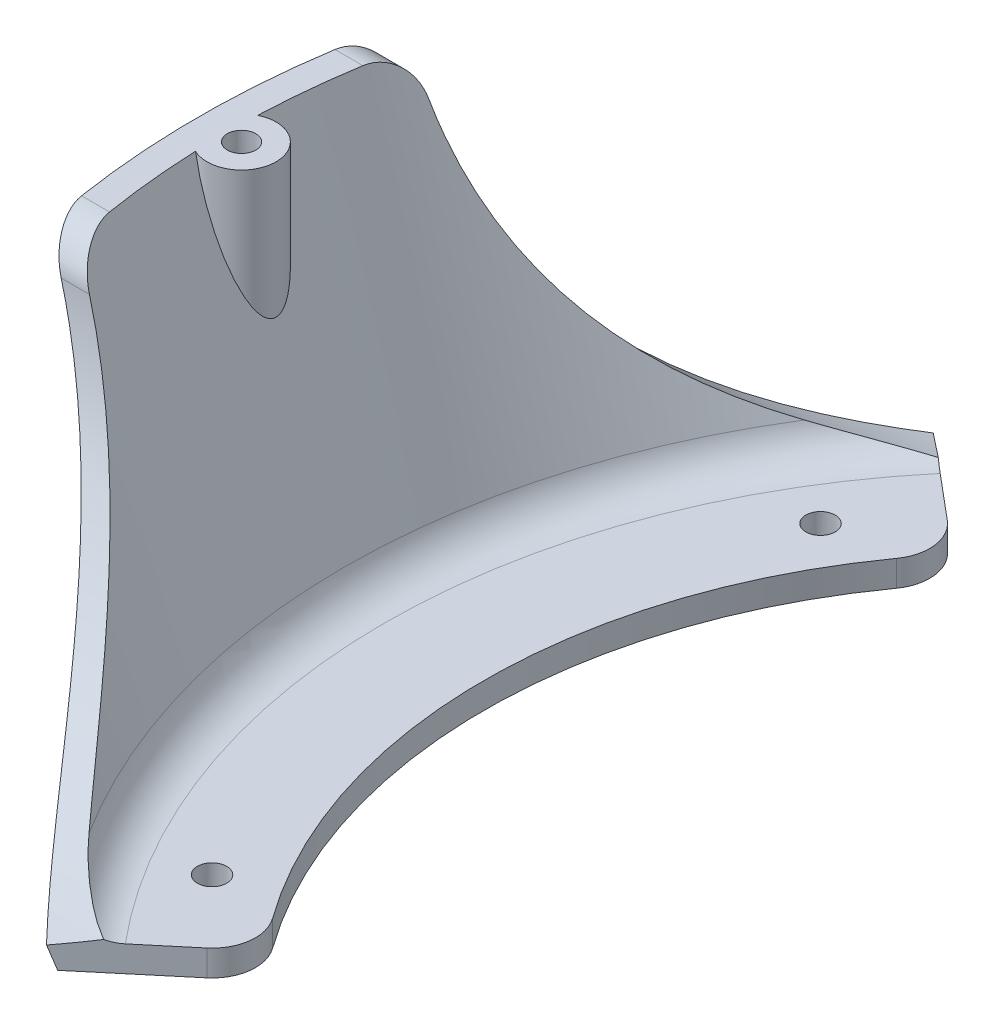
SolidWorks part; units mm, degrees
ref_plane "Plan de face" through (0, 0, 0) normal (0, 0, 1) x (1, 0, 0)
ref_plane "Plan de dessus" through (0, 0, 0) normal (0, 1, 0) x (1, 0, 0)
ref_plane "Plan de droite" through (0, 0, 0) normal (1, 0, 0) x (0, 0, -1)
sketch "Esquisse1" plane through (0, 0, 0) normal (0, 0, 1) x (1, 0, 0)
  line L0 (0, 0) -> (-61.9153, 0) construction
  line L1 (-61.9153, 0) -> (-79, 0)
  line L2 (-79, 0) -> (-95, 43)
  line L3 (-95, 43) -> (-91.7991, 43)
  line L4 (-91.7991, 43) -> (-76.9153, 3)
  line L5 (-76.9153, 3) -> (-61.9153, 3)
  line L6 (-61.9153, 3) -> (-61.9153, 0)
  point P3 (-93.3995, 43)
  dimension "D1" = 3
  dimension "D2" = 3
  dimension "D3" = 43
  dimension "D4" = 79
  dimension "D5" = 15
  dimension "D6" = 95
ref_axis "Axe1" through (0, 0, 0) along (0, 1, 0)
revolve "Révolution1" add sketch "Esquisse1" angle 80 mid plane about axis through (0, 0, 0) along (0, 1, 0)
sketch "Esquisse3" plane through (0, 43, 0) normal (0, 1, 0) x (1, 0, 0)
  line L1 (45, 77.9423) -> (-90, 0) construction
  line L2 (-90, 0) -> (45, -77.9423) construction
  line L3 (45, -77.9423) -> (45, 77.9423) construction
  circle A0 centre (0, 0) radius 45 construction
  circle A1 centre (-90, 0) radius 4
  dimension "D2" = 8
  dimension "D1" = 90
extrude "Boss.-Extru.1" add sketch "Esquisse3" against normal up to next
hole_wizard "Trou pour taraudage pour trou taraudé M41" positions "Esquisse4" profile "Esquisse5" hole size "M4" standard "ISO" end condition through all
sketch "Esquisse4" plane through (0, 43, 0) normal (0, 1, 0) x (1, 0, 0)
  point P3 (-90, 0)
sketch "Esquisse5" plane through (-90, 43, 0) normal (1, 0, 0) x (0, 0, 1)
  line L0 (0, 0) -> (0, 43)
  line L1 (0, 43) -> (1.65, 43)
  line L2 (1.65, 43) -> (1.65, 0)
  line L5 (1.65, 0) -> (0, 0)
  line L11 (0, -6.35) -> (0, 107.95) construction
  dimension "Diamètre du perçage jusqu'au prochain" = 3.3
  dimension "Profondeur du perçage jusqu'au prochain" = 43
hole_wizard "Dégagement M31" positions "Esquisse6" profile "Esquisse7" hole size "M3" standard "ISO" end condition through all
sketch "Esquisse6" plane through (0, 3, 0) normal (0, 1, 0) x (1, 0, 0)
  line L0 (-58.168, 35.25) -> (-1.4434, 68) construction
  line L1 (-1.4434, 68) -> (59.6114, 32.75) construction
  line L2 (59.6114, 32.75) -> (59.6114, -32.75) construction
  line L3 (59.6114, -32.75) -> (-1.4434, -68) construction
  line L4 (-1.4434, -68) -> (-58.168, -35.25) construction
  line L5 (-58.168, -35.25) -> (-58.168, 35.25) construction
  line L7 (-58.168, -35.25) -> (59.6114, -32.75) construction
  line L8 (59.6114, -32.75) -> (-1.4434, 68) construction
  line L9 (-1.4434, 68) -> (-58.168, -35.25) construction
  line L11 (-58.168, 35.25) -> (-1.4434, -68) construction
  line L12 (-1.4434, -68) -> (59.6114, 32.75) construction
  line L13 (59.6114, 32.75) -> (-58.168, 35.25) construction
  line L15 (-58.168, -35.25) -> (29.084, 17.625) construction
  line L17 (-58.168, 35.25) -> (29.084, -17.625) construction
  point P14 (-58.168, 35.25)
  point P24 (-58.168, -35.25)
  point P64 (59.6114, 0)
  dimension "D1" = 65.5
  dimension "D2" = 70.5
sketch "Esquisse7" plane through (-58.168, 3, -35.25) normal (1, 0, 0) x (0, 0, 1)
  line L0 (0, 0) -> (0, 3)
  line L1 (0, 3) -> (1.7, 3)
  line L2 (1.7, 3) -> (1.7, 0)
  line L5 (1.7, 0) -> (0, 0)
  line L11 (0, -6.35) -> (0, 107.95) construction
  dimension "Diamètre du perçage jusqu'au prochain" = 3.4
  dimension "Profondeur du perçage jusqu'au prochain" = 3
sketch "Esquisse8" plane through (0, 0, 0) normal (1, 0, 0) x (0, 0, -1)
  circle A0 centre (-61.0648, 43) radius 41.6549
  circle A1 centre (61.0648, 43) radius 41.6549
extrude "Enlèv. mat.-Extru.1" cut sketch "Esquisse8" against normal through all
fillet "Congé1" radius 5 5 edges at (-76.9153, 3, 0) (-91.3598, 43, -19.4099) (-91.3598, 43, 19.4099) (-47.4299, 1.5, -39.7984) (-47.4299, 1.5, 39.7984)
